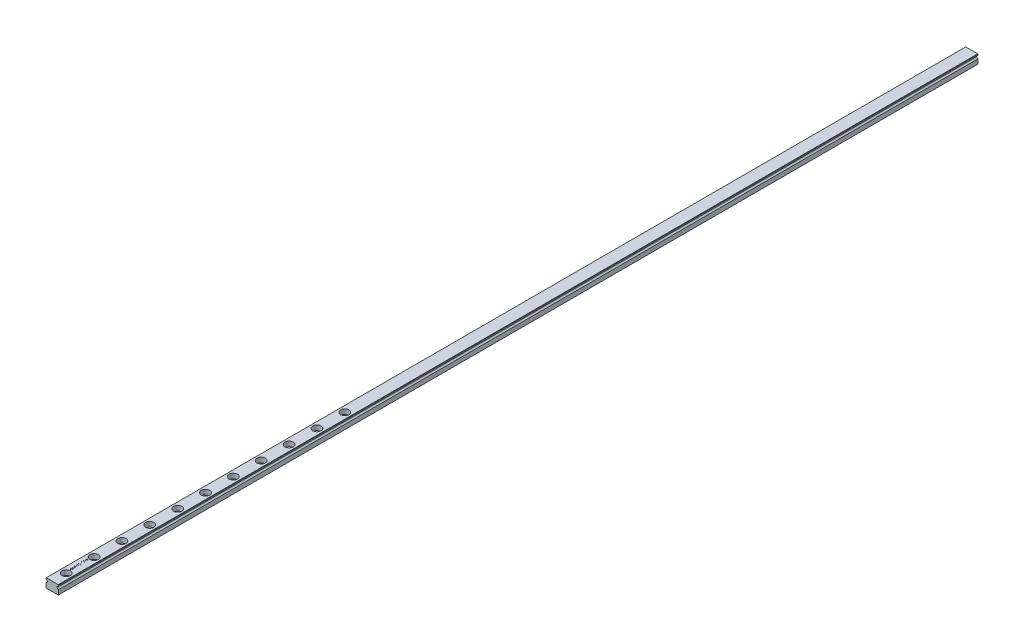
SolidWorks part; units mm, degrees
material "镀铬不锈钢"
ref_plane "前视基准面" through (0, 0, 0) normal (0, 0, 1) x (1, 0, 0)
ref_plane "上视基准面" through (0, 0, 0) normal (0, 1, 0) x (1, 0, 0)
ref_plane "右视基准面" through (0, 0, 0) normal (1, 0, 0) x (0, 0, -1)
sketch "草图1" plane through (0, 0, 0) normal (0, 0, 1) x (1, 0, 0)
  line L2 (4.5, 5.5) -> (4.5, 6.3)
  line L3 (-4.3, 6.5) -> (-4.5, 6.3)
  line L4 (4.5, 0.2) -> (4.5, 3.5)
  line L5 (4.3, 6.5) -> (-4.3, 6.5)
  line L6 (4.5, 6.3) -> (4.3, 6.5)
  line L7 (-4.3, 0) -> (0.2, 0)
  line L8 (4.3, 0) -> (4.5, 0.2)
  line L9 (0.8, 0) -> (4.3, 0)
  line L10 (-4.5, 0.2) -> (-4.3, 0)
  line L11 (0, 6.5) -> (0, 0) construction
  line L12 (-4.5, 3.5) -> (-4.5, 0.2)
  line L13 (-4.5, 6.3) -> (-4.5, 5.5)
  arc A0 (-4.5, 3.5) -> (-4.5, 5.5) centre (-4.5, 4.5) ccw
  arc A1 (0.8, 0) -> (0.2, 0) centre (0.5, 0) ccw
  arc A2 (4.5, 5.5) -> (4.5, 3.5) centre (4.5, 4.5) ccw
extrude "凸台-拉伸1" add sketch "草图1" against normal blind 220
hole_wizard "M3 六角凹头螺钉的柱形沉头孔1" positions "草图3" profile "草图2" counterbore size "M3" standard "ISO" end condition through all
sketch "草图3" plane through (0.7549, 6.5, 19.3435) normal (0, 1, 0) x (-1, 0, 0)
  point P0 (0.7549, -29.3435)
  dimension "D1" = 10
sketch "草图2" plane through (0, 6.5, -10) normal (1, 0, 0) x (0, 0, 1)
  line L0 (0, 0) -> (0, 6.5)
  line L1 (0, 6.5) -> (1.75, 6.5)
  line L3 (1.75, 6.5) -> (1.75, 3.5)
  line L4 (1.75, 3.5) -> (3, 3.5)
  line L5 (3, 3.5) -> (3, 0)
  line L7 (3, 0) -> (0, 0)
  line L11 (0, -6.35) -> (0, 107.95) construction
  dimension "通孔孔直径" = 3.5
  dimension "通孔孔深度" = 6.5
  dimension "柱形沉头孔直径" = 6
  dimension "柱形沉头孔深度" = 3.5
pattern_linear "阵列(线性)1" count 11 spacing 20 along (0, 0, -1) of "M3 六角凹头螺钉的柱形沉头孔1"
sketch "草图6" plane through (0, 6.5, 0) normal (0, 1, 0) x (1, 0, 0)
  line L0 (0, 10) -> (0, 30) construction
  text T0 "HIWIN MGN9" font "Century Gothic" height 1.5
extrude "切除-拉伸1" cut sketch "草图6" against normal blind 0.1
sketch "草图7" plane through (0, 0, -220) normal (0, 0, -1) x (-1, 0, 0)
  line L11 (-4.3, 0) -> (-0.8, 0)
  line L12 (-0.2, 0) -> (4.3, 0)
  line L13 (4.3, 0) -> (4.5, 0.2)
  line L14 (4.5, 0.2) -> (4.5, 3.5)
  line L15 (4.5, 5.5) -> (4.5, 6.3)
  line L16 (4.5, 6.3) -> (4.3, 6.5)
  line L17 (4.3, 6.5) -> (-4.3, 6.5)
  line L18 (-4.3, 6.5) -> (-4.5, 6.3)
  line L19 (-4.5, 6.3) -> (-4.5, 5.5)
  line L20 (-4.5, 3.5) -> (-4.5, 0.2)
  line L21 (-4.5, 0.2) -> (-4.3, 0)
  line L22 (-4.3, 0) -> (-0.8, 0)
  line L23 (-0.2, 0) -> (4.3, 0)
  line L24 (4.3, 0) -> (4.5, 0.2)
  line L25 (4.5, 0.2) -> (4.5, 3.5)
  line L26 (4.5, 5.5) -> (4.5, 6.3)
  line L27 (4.5, 6.3) -> (4.3, 6.5)
  line L28 (4.3, 6.5) -> (-4.3, 6.5)
  line L29 (-4.3, 6.5) -> (-4.5, 6.3)
  line L30 (-4.5, 6.3) -> (-4.5, 5.5)
  line L31 (-4.5, 3.5) -> (-4.5, 0.2)
  line L32 (-4.5, 0.2) -> (-4.3, 0)
  arc A3 (-0.2, 0) -> (-0.8, 0) centre (-0.5, 0) ccw
  arc A4 (4.5, 5.5) -> (4.5, 3.5) centre (4.5, 4.5) ccw
  arc A5 (-4.5, 3.5) -> (-4.5, 5.5) centre (-4.5, 4.5) ccw
  arc A6 (-0.2, 0) -> (-0.8, 0) centre (-0.5, 0) ccw
  arc A7 (4.5, 5.5) -> (4.5, 3.5) centre (4.5, 4.5) ccw
  arc A8 (-4.5, 3.5) -> (-4.5, 5.5) centre (-4.5, 4.5) ccw
  dimension "D1" = 0
extrude "凸台-拉伸2" add sketch "草图7" along normal blind 440
